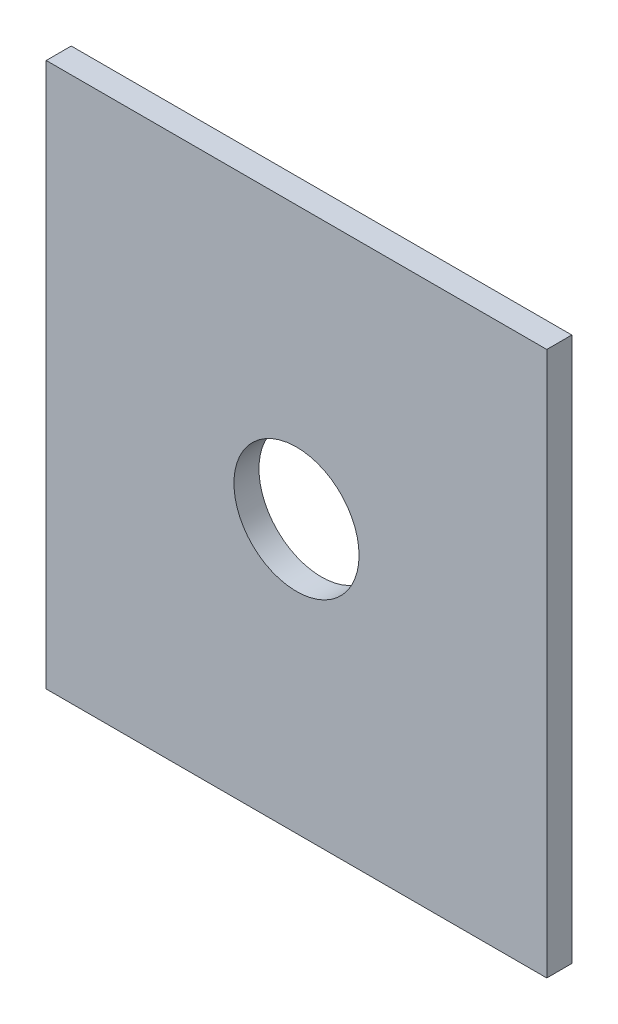
SolidWorks part; units mm, degrees
ref_plane "前视基准面" through (0, 0, 0) normal (0, 0, 1) x (1, 0, 0)
ref_plane "上视基准面" through (0, 0, 0) normal (0, 1, 0) x (1, 0, 0)
ref_plane "右视基准面" through (0, 0, 0) normal (1, 0, 0) x (0, 0, -1)
sketch "草图2" plane through (0, 0, 0) normal (0, 0, 1) x (1, 0, 0)
  line L1 (0, 0) -> (40, 0)
  line L2 (0, 0) -> (0, -43.5)
  line L3 (0, -43.5) -> (40, -43.5)
  line L4 (40, 0) -> (40, -43.5)
  dimension "D1" = 40
  dimension "D2" = 43.5
extrude "凸台-拉伸1" add sketch "草图2" along normal blind 2
sketch "草图3" plane through (0, 0, 2) normal (0, 0, 1) x (1, 0, 0)
  line L0 (0, -21.75) -> (20, -21.75) construction
  line L1 (0, 0) -> (0, -43.5) construction
  circle A0 centre (20, -21.75) radius 5
  dimension "D1" = 10
extrude "切除-拉伸1" cut sketch "草图3" against normal through all
